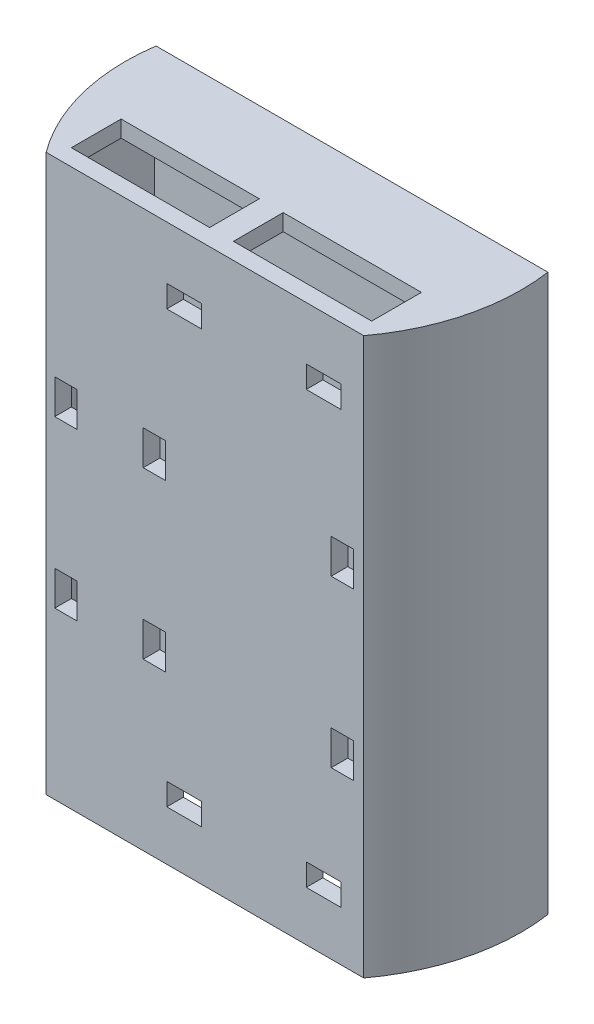
SolidWorks part; units mm, degrees
ref_plane "Front Plane" through (0, 0, 0) normal (0, 0, 1) x (1, 0, 0)
ref_plane "Top Plane" through (0, 0, 0) normal (0, 1, 0) x (1, 0, 0)
ref_plane "Right Plane" through (0, 0, 0) normal (1, 0, 0) x (0, 0, -1)
sketch "Sketch1" plane through (0, 0, 0) normal (0, 1, 0) x (1, 0, 0)
  line L10 (-45, 5.21) -> (45, 5.21)
  line L15 (-45, 5.21) -> (-45, -21.39)
  line L16 (-45, -21.39) -> (45, -21.39)
  line L17 (45, 5.21) -> (45, -21.39)
  line L18 (-40, -18.39) -> (40, -18.39)
  line L19 (-40, -18.39) -> (-40, 2.21)
  line L20 (-40, 2.21) -> (40, 2.21)
  line L21 (40, -18.39) -> (40, 2.21)
  circle A0 centre (0, 0) radius 35.81
  circle A1 centre (0, 0) radius 32.81
  point P13 (0, 0)
  point P14 (-35.7417, 2.21)
  point P15 (35.7417, 2.21)
  point P16 (41.7427, 2.21)
  point P17 (-42.2687, 2.21)
  dimension "D1" = 71.62
  dimension "D2" = 5.21
  dimension "D3" = 26.6
  dimension "D4" = 3
  dimension "D5" = 3
  dimension "D7" = 5
  dimension "D8" = 5
  dimension "D9" = 40
  dimension "D10" = 40
  dimension "D6" = 3
extrude "Boss-Extrude1" add sketch "Sketch1" along normal blind 97.62 contours A1 L20 A0 L18 | A1 L18 A0 L16 | L16 A1 L18 | A1 L10 A0 L20 | L20 A1 L10 | A1 L20 A0 L10 | A1 L18 A0 L20 | A1 L16 A0 L18
sketch "Sketch2" plane through (-23.61, 0, 21.39) normal (0, 0, -1) x (-1, 0, 0)
  line L1 (-50.4492, 30) -> (-46.4492, 30)
  line L2 (-50.4492, 30) -> (-50.4492, 36.25)
  line L3 (-50.4492, 36.25) -> (-46.4492, 36.25)
  line L4 (-46.4492, 30) -> (-46.4492, 36.25)
  line L5 (-50.4492, 30) -> (-46.4492, 36.25) construction
  line L6 (-50.4492, 36.25) -> (-46.4492, 30) construction
  line L7 (-18.4492, 15) -> (-46.4492, 15)
  line L8 (-18.4492, 15) -> (-18.4492, 85)
  line L9 (-18.4492, 85) -> (-46.4492, 85)
  line L10 (-46.4492, 15) -> (-46.4492, 85)
  line L14 (-59.039, 97.62) -> (-59.039, 0) construction
  line L15 (-16.4492, 30) -> (-16.4492, 36.25)
  line L16 (-16.4492, 30) -> (-12.4492, 30)
  line L17 (-12.4492, 30) -> (-12.4492, 36.25)
  line L18 (-16.4492, 36.25) -> (-12.4492, 36.25)
  line L19 (-16.4492, 60) -> (-16.4492, 66.25)
  line L20 (-16.4492, 60) -> (-12.4492, 60)
  line L21 (-12.4492, 60) -> (-12.4492, 66.25)
  line L22 (-16.4492, 66.25) -> (-12.4492, 66.25)
  line L23 (-50.4492, 60) -> (-50.4492, 66.25)
  line L24 (-50.4492, 60) -> (-46.4492, 60)
  line L25 (-46.4492, 60) -> (-46.4492, 66.25)
  line L26 (-50.4492, 66.25) -> (-46.4492, 66.25)
  line L27 (-0.4492, 30) -> (-0.4492, 36.25)
  line L28 (-0.4492, 30) -> (3.5508, 30)
  line L29 (3.5508, 30) -> (3.5508, 36.25)
  line L30 (-0.4492, 36.25) -> (3.5508, 36.25)
  line L31 (-0.4492, 60) -> (-0.4492, 66.25)
  line L32 (-0.4492, 60) -> (3.5508, 60)
  line L33 (3.5508, 60) -> (3.5508, 66.25)
  line L34 (-0.4492, 66.25) -> (3.5508, 66.25)
  line L35 (-50.4492, 60) -> (-50.4492, 66.25)
  line L36 (-50.4492, 60) -> (-46.4492, 60)
  line L37 (-46.4492, 60) -> (-46.4492, 66.25)
  line L38 (-50.4492, 66.25) -> (-46.4492, 66.25)
  line L39 (-32.4492, 85) -> (-32.4492, 15)
  line L40 (-16.7073, 9) -> (-22.9573, 9)
  line L41 (-16.7073, 9) -> (-16.7073, 13)
  line L42 (-16.7073, 13) -> (-22.9573, 13)
  line L43 (-22.9573, 9) -> (-22.9573, 13)
  line L44 (-48.191, 13) -> (-41.941, 13)
  line L45 (-41.941, 9) -> (-41.941, 13)
  line L46 (-48.191, 9) -> (-41.941, 9)
  line L47 (-48.191, 9) -> (-48.191, 13)
  line L48 (-46.4492, 50) -> (-18.4492, 50)
  line L49 (-48.191, 91) -> (-48.191, 87)
  line L50 (-48.191, 91) -> (-41.941, 91)
  line L51 (-41.941, 91) -> (-41.941, 87)
  line L52 (-48.191, 87) -> (-41.941, 87)
  line L53 (-16.7073, 87) -> (-22.9573, 87)
  line L54 (-22.9573, 91) -> (-22.9573, 87)
  line L55 (-16.7073, 91) -> (-22.9573, 91)
  line L56 (-16.7073, 91) -> (-16.7073, 87)
  line L57 (11.819, 0) -> (-59.039, 0) construction
  line L58 (-59.039, 97.62) -> (-59.039, 0)
  line L59 (11.819, 0) -> (-59.039, 0)
  line L60 (-52.3297, 97.62) -> (-52.3297, 0) construction
  line L61 (-52.3297, 97.62) -> (-52.3297, 0)
  point P0 (-48.4492, 33.125)
  point P14 (-46.4492, 33.125)
  dimension "D1" = 22.8392
  dimension "D2" = 4
  dimension "D3" = 6.25
  dimension "D4" = 30
  dimension "D5" = 70
  dimension "D6" = 28
  dimension "D7" = 9
  dimension "D8" = 0
  dimension "D13" = 6.25
  dimension "D14" = 4
  dimension "D15" = 4.1387
  dimension "D17" = 31.4837
  dimension "D9" = 2
  dimension "D10" = 2
  dimension "D11" = 2
  dimension "D12" = 2
extrude "Cut-Extrude1" cut sketch "Sketch2" along normal blind 3 contours L31 L34 L33 L32 | L15 L18 L17 L16 | L19 L22 L21 L20 | L55 L56 L53 L54 | L52 L49 L50 L51 | L23 L26 L10 L24 | L46 L47 L44 L45 | L40 L43 L42 L41 | L30 L29 L28 L27 | L3 L4 L1 L2
sketch "Sketch5" plane through (0, 97.62, 0) normal (0, 1, 0) x (1, 0, 0)
  line L0 (0, 0) -> (0, -18)
  line L1 (-27.1602, -18.39) -> (-2.1602, -18.39)
  line L2 (35.429, 5.21) -> (-35.429, 5.21)
  line L3 (35.429, 5.21) -> (-35.429, 5.21)
  line L6 (-27.1602, -18.39) -> (-27.1602, -9.39)
  line L7 (-27.1602, -9.39) -> (-2.1602, -9.39)
  line L8 (-2.1602, -18.39) -> (-2.1602, -9.39)
  line L9 (27.1602, -9.39) -> (2.1602, -9.39)
  line L10 (2.1602, -18.39) -> (2.1602, -9.39)
  line L11 (27.1602, -18.39) -> (2.1602, -18.39)
  line L12 (27.1602, -18.39) -> (27.1602, -9.39)
  line L13 (-27.1718, -18.39) -> (27.1718, -18.39) construction
  line L15 (-28.7197, -21.39) -> (28.7197, -21.39)
  line L16 (-28.7197, -21.39) -> (28.7197, -21.39)
  arc A0 (-32.7355, 2.21) -> (-27.1718, -18.39) centre (0, 0) ccw construction
  arc A1 (-32.7355, 2.21) -> (-27.1718, -18.39) centre (0, 0) ccw
  arc A2 (28.7197, -21.39) -> (35.429, 5.21) centre (0, 0) ccw
  arc A3 (28.7197, -21.39) -> (35.429, 5.21) centre (0, 0) ccw
  arc A6 (-35.429, 5.21) -> (-28.7197, -21.39) centre (0, 0) ccw
  arc A7 (-35.429, 5.21) -> (-28.7197, -21.39) centre (0, 0) ccw
  point P20 (0, 0)
  dimension "D2" = 25
  dimension "D3" = 9
  dimension "D4" = 0
  dimension "D1" = 0
extrude "Boss-Extrude4" add sketch "Sketch5" along normal blind 3
